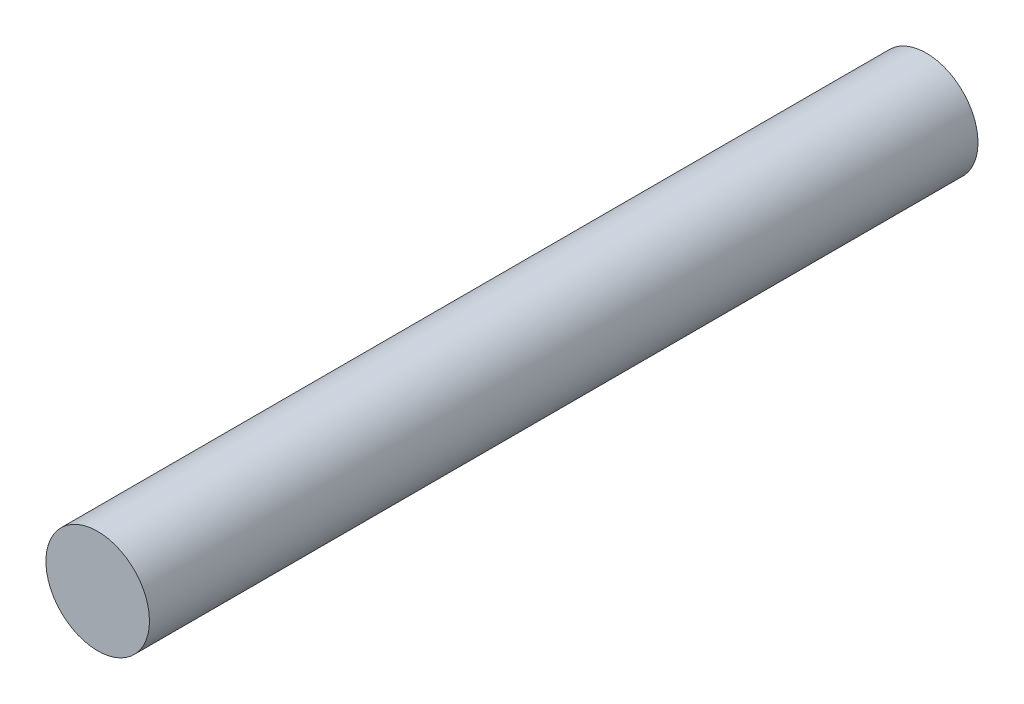
SolidWorks part; units mm, degrees
ref_plane "Front Plane" through (0, 0, 0) normal (0, 0, 1) x (1, 0, 0)
ref_plane "Top Plane" through (0, 0, 0) normal (0, 1, 0) x (1, 0, 0)
ref_plane "Right Plane" through (0, 0, 0) normal (1, 0, 0) x (0, 0, -1)
sketch "Sketch1" plane through (0, 0, 0) normal (0, 0, 1) x (1, 0, 0)
  circle A0 centre (0, 0) radius 1.5875
  dimension "D1" = 3.175
extrude "Boss-Extrude1" add sketch "Sketch1" along normal blind 25.4
sketch "Sketch2" plane through (0, 0, 0) normal (0, 0, -1) x (-1, 0, 0)
  circle A0 centre (0, 0) radius 1.016
  dimension "D1" = 2.032
extrude "Cut-Extrude1" cut sketch "Sketch2" against normal blind 5.08
